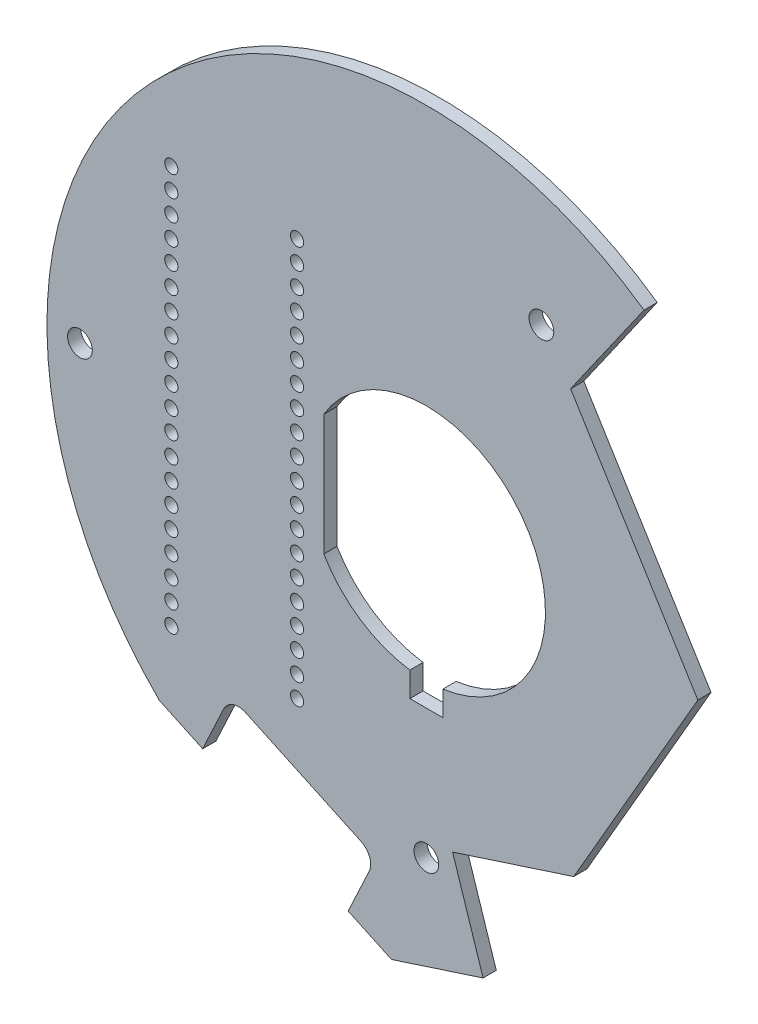
SolidWorks part; units mm, degrees
ref_plane "Front Plane" through (0, 0, 0) normal (0, 0, 1) x (1, 0, 0)
ref_plane "Top Plane" through (0, 0, 0) normal (0, 1, 0) x (1, 0, 0)
ref_plane "Right Plane" through (0, 0, 0) normal (1, 0, 0) x (0, 0, -1)
sketch "Sketch1" plane through (0, 0, 0) normal (0, 0, 1) x (1, 0, 0)
  line L0 (26.3845, 37.681) -> (17.4865, 24.9733)
  line L1 (17.4865, 24.9733) -> (32.909, 0)
  line L2 (32.909, 0) -> (46, 0)
  line L3 (32.909, 0) -> (17.8666, -26.0541)
  line L4 (17.8666, -26.0541) -> (3.1813, -30.8256)
  line L5 (3.1813, -30.8256) -> (7.8903, -45.3182)
  line L6 (22.6369, -27.7918) -> (34.0119, -8.0897) construction
  line L7 (6.6285, -34.9629) -> (15.1881, -32.1817) construction
  line L8 (6.6285, -34.9629) -> (8.9462, -42.0958) construction
  line L10 (17.4865, 24.9733) -> (0, 0) construction
  line L11 (-32.3723, -32.6808) -> (-4.2265, -45.8054)
  line L12 (-26.3498, -37.6959) -> (-11.9395, -44.4156) construction
  circle A0 centre (0, 0) radius 46
  point P17 (10.524, -28.4399)
  dimension "D1" = 92
  dimension "D2" = 5
  dimension "D3" = 18
  dimension "D4" = 55
  dimension "D5" = 5
  dimension "D6" = 2
  dimension "D7" = 2
extrude "Boss-Extrude1" add sketch "Sketch1" along normal blind 1.6
sketch "Sketch2" plane through (0, 0, 1.6) normal (0, 0, 1) x (1, 0, 0)
  line L2 (-12.1394, 7.2497) -> (-12.1394, -7.2497) construction
  line L3 (-12.4394, 7.332) -> (-12.4394, -7.332)
  arc A0 (-12.1394, -7.2497) -> (-12.1394, 7.2497) centre (0, 0) ccw construction
  arc A3 (-12.1394, -7.2497) -> (-12.1394, 7.2497) centre (0, 0) ccw construction
  arc A4 (-12.4394, -7.332) -> (-12.4394, 7.332) centre (0, 0) ccw
  dimension "D1" = 0.3
extrude "Cut-Extrude1" cut sketch "Sketch2" against normal blind 1.6
sketch "Sketch3" plane through (0, 0, 1.6) normal (0, 0, 1) x (1, 0, 0)
  line L0 (-2, -14.3002) -> (-2, -17.3002)
  line L1 (-2, -17.3002) -> (2, -17.3002)
  line L2 (2, -17.3002) -> (2, -14.3002)
  line L3 (2, -14.3002) -> (-2, -14.3002)
  line L4 (0, 0) -> (0, -14.3002) construction
  arc A0 (-12.4394, -7.332) -> (-12.4394, 7.332) centre (0, 0) ccw construction
  dimension "D1" = 4
  dimension "D2" = 3
extrude "Cut-Extrude2" cut sketch "Sketch3" against normal blind 1.6
sketch "Sketch4" plane through (0, 0, 1.6) normal (0, 0, 1) x (1, 0, 0)
  line L0 (13.9464, 29.9082) -> (0, 0) construction
  line L1 (0, 0) -> (0, -33) construction
  circle A0 centre (-42, 0) radius 1.5
  circle A1 centre (13.9464, 29.9082) radius 1.5
  circle A2 centre (0, -33) radius 1.5
  circle A3 centre (0, 0) radius 42 construction
  circle A4 centre (0, 0) radius 33 construction
  dimension "D1" = 3
  dimension "D2" = 66
  dimension "D3" = 84
  dimension "D4" = 155
extrude "Cut-Extrude3" cut sketch "Sketch4" against normal blind 5
sketch "Sketch5" plane through (0, 0, 1.6) normal (0, 0, 1) x (1, 0, 0)
  circle A0 centre (-30.9194, -24.13) radius 0.8 construction
  circle A1 centre (-30.9194, -24.13) radius 0.8
  circle A2 centre (-15.6794, -24.13) radius 0.8 construction
  circle A3 centre (-15.6794, -24.13) radius 0.8
  circle A4 centre (-30.9194, -21.59) radius 0.8
  circle A5 centre (-15.6794, -21.59) radius 0.8
  circle A6 centre (-30.9194, -19.05) radius 0.8
  circle A7 centre (-15.6794, -19.05) radius 0.8
  circle A8 centre (-30.9194, -16.51) radius 0.8
  circle A9 centre (-15.6794, -16.51) radius 0.8
  circle A10 centre (-30.9194, -13.97) radius 0.8
  circle A11 centre (-15.6794, -13.97) radius 0.8
  circle A12 centre (-30.9194, -11.43) radius 0.8
  circle A13 centre (-15.6794, -11.43) radius 0.8
  circle A14 centre (-30.9194, -8.89) radius 0.8
  circle A15 centre (-15.6794, -8.89) radius 0.8
  circle A16 centre (-30.9194, -6.35) radius 0.8
  circle A17 centre (-15.6794, -6.35) radius 0.8
  circle A18 centre (-30.9194, -3.81) radius 0.8
  circle A19 centre (-15.6794, -3.81) radius 0.8
  circle A20 centre (-30.9194, -1.27) radius 0.8
  circle A21 centre (-15.6794, -1.27) radius 0.8
  circle A22 centre (-30.9194, 1.27) radius 0.8
  circle A23 centre (-15.6794, 1.27) radius 0.8
  circle A24 centre (-30.9194, 3.81) radius 0.8
  circle A25 centre (-15.6794, 3.81) radius 0.8
  circle A26 centre (-30.9194, 6.35) radius 0.8
  circle A27 centre (-15.6794, 6.35) radius 0.8
  circle A28 centre (-30.9194, 8.89) radius 0.8
  circle A29 centre (-15.6794, 8.89) radius 0.8
  circle A30 centre (-30.9194, 11.43) radius 0.8
  circle A31 centre (-15.6794, 11.43) radius 0.8
  circle A32 centre (-30.9194, 13.97) radius 0.8
  circle A33 centre (-15.6794, 13.97) radius 0.8
  circle A34 centre (-30.9194, 16.51) radius 0.8
  circle A35 centre (-15.6794, 16.51) radius 0.8
  circle A36 centre (-30.9194, 19.05) radius 0.8
  circle A37 centre (-15.6794, 19.05) radius 0.8
  circle A38 centre (-30.9194, 21.59) radius 0.8
  circle A39 centre (-15.6794, 21.59) radius 0.8
  circle A40 centre (-30.9194, 24.13) radius 0.8
  circle A41 centre (-15.6794, 24.13) radius 0.8
  dimension "D1" = 20
  dimension "D2" = 2.54
extrude "Cut-Extrude4" cut sketch "Sketch5" against normal blind 10
sketch "Sketch6" plane through (0, 0, 1.6) normal (0, 0, 1) x (1, 0, 0)
  line L0 (-4.2265, -45.8054) -> (6.8764, -42.1979)
  line L1 (3.1813, -30.8256) -> (7.8903, -45.3182) construction
  line L2 (6.8764, -42.1979) -> (21.0843, -57.4878)
  line L3 (21.0843, -57.4878) -> (-10.0292, -66.1665)
  line L4 (-10.0292, -66.1665) -> (-4.2265, -45.8054)
  line L5 (2.6978, -45.2499) -> (-3.0085, -47.104) construction
extrude "Cut-Extrude5" cut sketch "Sketch6" against normal blind 10
sketch "Sketch7" plane through (0, 0, 1.6) normal (0, 0, 1) x (1, 0, 0)
  line L0 (-27.1177, -35.1311) -> (-23.7368, -27.8806)
  line L1 (-32.3723, -32.6808) -> (-4.2265, -45.8054) construction
  line L2 (-23.7368, -27.8806) -> (-6.1, -36.1047)
  line L3 (-6.1, -36.1047) -> (-9.481, -43.3552)
  line L4 (-9.481, -43.3552) -> (-27.1177, -35.1311)
  line L5 (-13.9515, -43.4773) -> (-11.8384, -38.9458) construction
  line L6 (-22.2247, -34.1026) -> (-24.3378, -38.6341) construction
  dimension "D1" = 4
  dimension "D2" = 4
  dimension "D3" = 8
extrude "Cut-Extrude6" cut sketch "Sketch7" against normal blind 5
fillet "Fillet1" radius 2 2 edges at (-6.1, -36.1047, 0.8) (-23.7368, -27.8806, 0.8)
sketch "Sketch8" plane through (0, 0, 0) normal (0, 0, -1) x (-1, 0, 0)
  circle A0 centre (-28.7953, 0) radius 3.5 construction
  circle A1 centre (-28.7953, 0) radius 3.5
  circle A2 centre (0, -33) radius 3.5 construction
  circle A3 centre (0, -33) radius 3.5
  circle A4 centre (29.6985, -29.6985) radius 3.5 construction
  circle A5 centre (29.6985, -29.6985) radius 3.5
  circle A6 centre (42, 0) radius 3.5 construction
  circle A7 centre (42, 0) radius 3.5
  circle A8 centre (-13.9464, 29.9082) radius 3.5 construction
  circle A9 centre (-13.9464, 29.9082) radius 3.5
  circle A10 centre (21, 36.3731) radius 3.5 construction
  circle A11 centre (21, 36.3731) radius 3.5
sketch "Sketch9" plane through (0, 0, 1.6) normal (0, 0, 1) x (1, 0, 0)
  circle A0 centre (0, 0) radius 36
  dimension "D1" = 72
